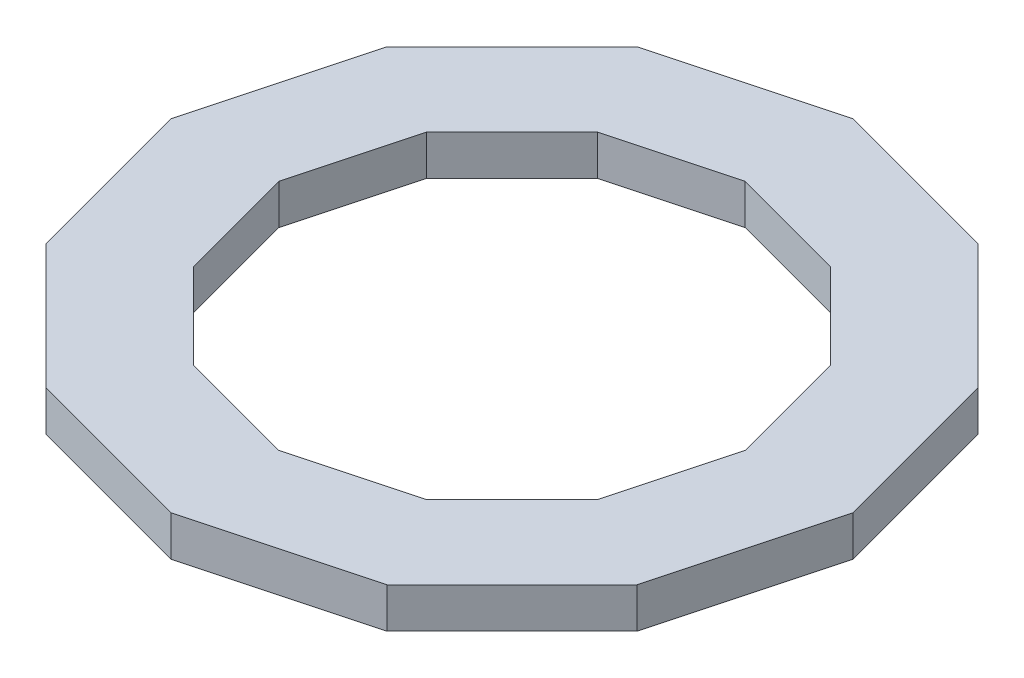
SolidWorks part; units mm, degrees
ref_plane "Front Plane" through (0, 0, 0) normal (0, 0, 1) x (1, 0, 0)
ref_plane "Top Plane" through (0, 0, 0) normal (0, 1, 0) x (1, 0, 0)
ref_plane "Right Plane" through (0, 0, 0) normal (1, 0, 0) x (0, 0, -1)
sketch "Sketch2" plane through (0, 0, 0) normal (0, 1, 0) x (1, 0, 0)
  line L0 (0, 0) -> (-110.6506, 0) construction
  line L1 (-161.9278, 0) -> (-140.2336, -80.9639)
  line L2 (-140.2336, -80.9639) -> (-80.9639, -140.2336)
  line L3 (-80.9639, -140.2336) -> (0, -161.9278)
  line L4 (0, -161.9278) -> (80.9639, -140.2336)
  line L5 (80.9639, -140.2336) -> (140.2336, -80.9639)
  line L6 (140.2336, -80.9639) -> (161.9278, 0)
  line L7 (161.9278, 0) -> (140.2336, 80.9639)
  line L8 (140.2336, 80.9639) -> (80.9639, 140.2336)
  line L9 (80.9639, 140.2336) -> (0, 161.9278)
  line L10 (0, 161.9278) -> (-80.9639, 140.2336)
  line L11 (-80.9639, 140.2336) -> (-140.2336, 80.9639)
  line L12 (-140.2336, 80.9639) -> (-161.9278, 0)
  line L13 (-110.6506, 0) -> (-95.8262, -55.3253)
  line L14 (-95.8262, -55.3253) -> (-55.3253, -95.8262)
  line L15 (-55.3253, -95.8262) -> (0, -110.6506)
  line L16 (0, -110.6506) -> (55.3253, -95.8262)
  line L17 (55.3253, -95.8262) -> (95.8262, -55.3253)
  line L18 (95.8262, -55.3253) -> (110.6506, 0)
  line L19 (110.6506, 0) -> (95.8262, 55.3253)
  line L20 (95.8262, 55.3253) -> (55.3253, 95.8262)
  line L21 (55.3253, 95.8262) -> (0, 110.6506)
  line L22 (0, 110.6506) -> (-55.3253, 95.8262)
  line L23 (-55.3253, 95.8262) -> (-95.8262, 55.3253)
  line L24 (-95.8262, 55.3253) -> (-110.6506, 0)
  line L25 (-161.9278, 0) -> (-110.6506, 0) construction
  circle A0 centre (0, 0) radius 156.4102 construction
  circle A1 centre (0, 0) radius 106.8802 construction
  dimension "D1" = 83.82
  dimension "D2" = 49.53
extrude "Boss-Extrude2" add sketch "Sketch2" along normal blind 19.05 separate body
